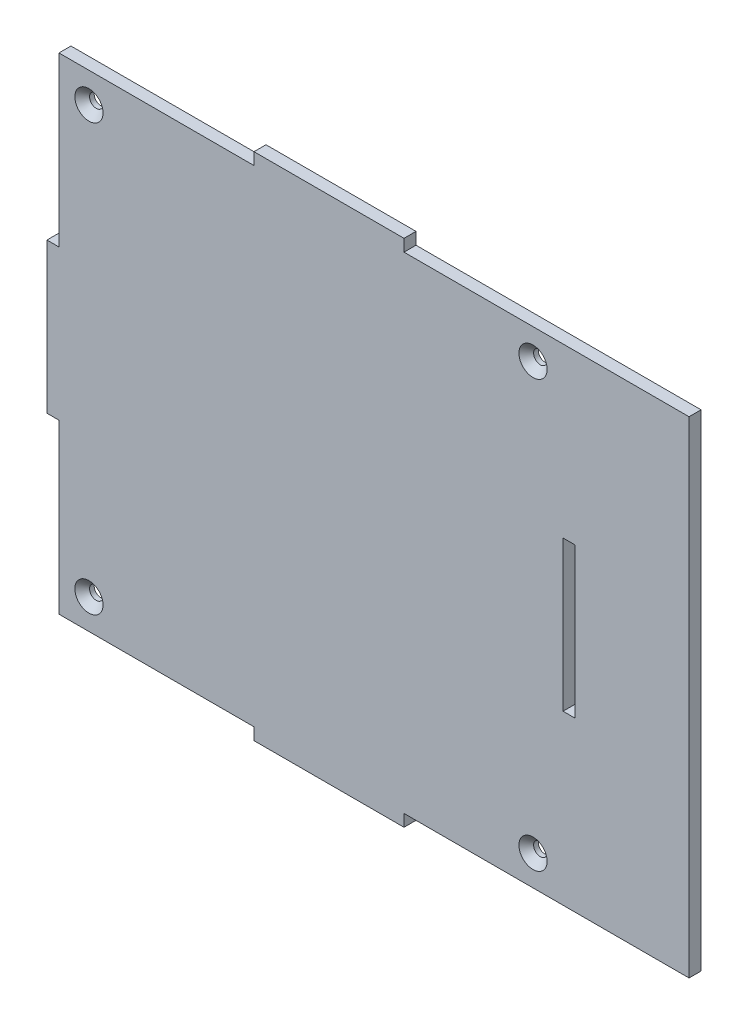
SolidWorks part; units mm, degrees
ref_plane "Front Plane" through (0, 0, 0) normal (0, 0, 1) x (1, 0, 0)
ref_plane "Top Plane" through (0, 0, 0) normal (0, 1, 0) x (1, 0, 0)
ref_plane "Right Plane" through (0, 0, 0) normal (1, 0, 0) x (0, 0, -1)
sketch "Sketch1" plane through (0, 0, 0) normal (0, 0, 1) x (1, 0, 0)
  line L1 (0, -25) -> (0, 25)
  line L2 (0, 25) -> (4, 25)
  line L3 (4, 25) -> (4, 81)
  line L4 (4, 81) -> (69, 81)
  line L5 (69, 81) -> (69, 85)
  line L6 (69, 85) -> (119, 85)
  line L7 (119, 85) -> (119, 81)
  line L8 (119, 81) -> (214, 81)
  line L9 (214, 81) -> (214, -81)
  line L16 (0, 0) -> (214, 0)
  line L17 (119, -81) -> (214, -81)
  line L18 (119, -85) -> (119, -81)
  line L19 (69, -85) -> (119, -85)
  line L20 (69, -81) -> (69, -85)
  line L21 (4, -81) -> (69, -81)
  line L22 (4, -25) -> (4, -81)
  line L23 (0, -25) -> (4, -25)
  dimension "D1" = 4
  dimension "D2" = 4
  dimension "D3" = 25
  dimension "D4" = 50
  dimension "D5" = 85
  dimension "D6" = 65
  dimension "D7" = 95
extrude "Boss-Extrude1" add sketch "Sketch1" along normal blind 4 contours L1 L16 L9 L8 L7 L6 L5 L4 L3 L2 | L1 L23 L22 L21 L20 L19 L18 L17 L9 L16
sketch "Sketch2" plane through (0, 0, 4) normal (0, 0, 1) x (1, 0, 0)
  line L0 (174, 0) -> (0, 0)
  line L1 (172, -25) -> (176, -25)
  line L2 (172, -25) -> (172, 25)
  line L3 (172, 25) -> (176, 25)
  line L4 (176, -25) -> (176, 25)
  line L5 (172, -25) -> (176, 25) construction
  line L6 (172, 25) -> (176, -25) construction
  line L7 (0, -25) -> (0, 25) construction
  line L8 (4, 25) -> (4, 81) construction
  point P0 (174, 0)
  dimension "D1" = 4
  dimension "D2" = 50
  dimension "D3" = 168
extrude "Cut-Extrude1" cut sketch "Sketch2" against normal up to next
sketch "Sketch3" plane through (0, 0, 4) normal (0, 0, 1) x (1, 0, 0)
  line L1 (14, -71) -> (162, -71)
  line L2 (14, -71) -> (14, 71)
  line L3 (14, 71) -> (162, 71)
  line L4 (162, -71) -> (162, 71)
  line L5 (4, 25) -> (4, 81) construction
  line L6 (172, -25) -> (172, 25) construction
  line L8 (4, 81) -> (69, 81) construction
  line L9 (119, -81) -> (214, -81) construction
  dimension "D1" = 10
  dimension "D2" = 10
  dimension "D3" = 10
  dimension "D4" = 10
hole_wizard "CSK for M4 Countersunk Flat Head Screw1" positions "3DSketch1" profile "Sketch4" countersink size "M4" standard "ISO" end condition up to next
sketch3d "3DSketch1"
  point P0 (14, 71, 4)
  point P3 (162, 71, 4)
  point P6 (162, -71, 4)
  point P9 (14, -71, 4)
sketch "Sketch4" plane through (14, 71, 4) normal (1, 0, 0) x (0, -1, 0)
  line L0 (0, 0) -> (0, 4)
  line L1 (0, 4) -> (2.25, 4)
  line L2 (2.25, 4) -> (2.25, 2.45)
  line L3 (2.25, 2.45) -> (4.7, 0)
  line L5 (4.7, 0) -> (0, 0)
  line L6 (-2.25, 2.45) -> (-4.7, 0) construction
  line L11 (0, -6.35) -> (0, 107.95) construction
  dimension "Thru Hole Dia." = 4.5
  dimension "Thru Hole Depth" = 4
  dimension "Near C'Sink Dia." = 9.4
  dimension "Near C'Sink Angle" = 90
